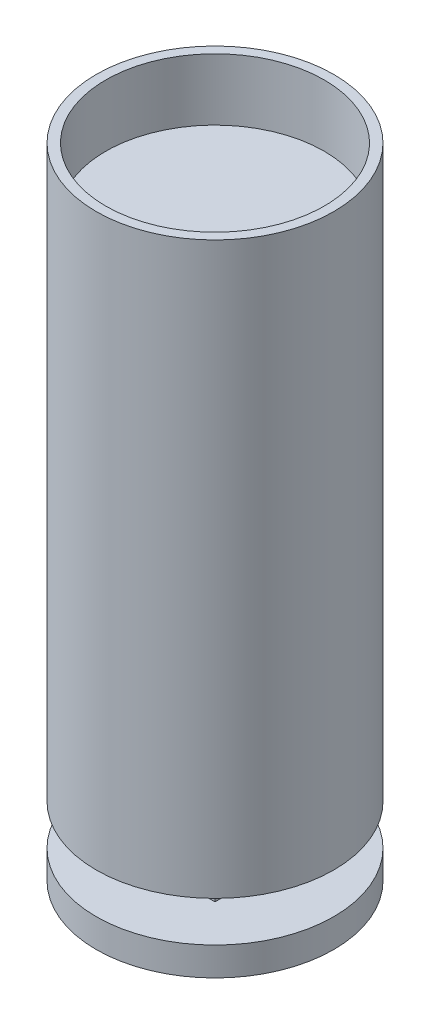
SolidWorks part; units mm, degrees
ref_plane "Front Plane" through (0, 0, 0) normal (0, 0, 1) x (1, 0, 0)
ref_plane "Top Plane" through (0, 0, 0) normal (0, 1, 0) x (1, 0, 0)
ref_plane "Right Plane" through (0, 0, 0) normal (1, 0, 0) x (0, 0, -1)
sketch "Sketch1" plane through (0, 0, 0) normal (0, 1, 0) x (1, 0, 0)
  line L0 (0, 12.3074) -> (0, -10.2003) construction
  line L1 (-13.6004, 0) -> (10.8228, 0) construction
  line L7 (8.8388, -8.8388) -> (-8.8388, 8.8388) construction
  line L8 (8.8388, 8.8388) -> (-8.8388, -8.8388) construction
  circle A0 centre (0, 0) radius 12.5
  dimension "D1" = 25
extrude "Boss-Extrude1" add sketch "Sketch1" along normal mid plane 3
sketch "Sketch2" plane through (0, 1.5, 0) normal (0, 1, 0) x (1, 0, 0)
  line L1 (4.9, -4.9) -> (-4.9, -4.9)
  line L2 (4.9, -4.9) -> (4.9, 4.9)
  line L3 (4.9, 4.9) -> (-4.9, 4.9)
  line L4 (-4.9, -4.9) -> (-4.9, 4.9)
  line L5 (4.9, -4.9) -> (-4.9, 4.9) construction
  line L6 (4.9, 4.9) -> (-4.9, -4.9) construction
  point P0 (0, 0)
  dimension "D1" = 9.8
  dimension "D2" = 9.8
extrude "Boss-Extrude2" add sketch "Sketch2" along normal blind 4.25
ref_plane "Plane1" through (0, 3.625, 0) normal (0, 1, 0) x (1, 0, 0)
mirror "Mirror1" about plane through (0, 3.625, 0) normal (0, 1, 0) of "Boss-Extrude1"
sketch "Sketch3" plane through (0, 8.75, 0) normal (0, 1, 0) x (1, 0, 0)
  circle A0 centre (0, 0) radius 12.5
  point P0 (0, 0)
  dimension "D1" = 25
extrude "Boss-Extrude3" add sketch "Sketch3" along normal blind 47.5
sketch "Sketch4" plane through (0, 56.25, 0) normal (0, 1, 0) x (1, 0, 0)
  circle A0 centre (0, 0) radius 12.5
  dimension "D1" = 25
extrude "Boss-Extrude4" add sketch "Sketch4" along normal blind 3
sketch "Sketch5" plane through (0, 59.25, 0) normal (0, 1, 0) x (1, 0, 0)
  circle A0 centre (0, 0) radius 11.5
  circle A1 centre (0, 0) radius 12.5
  dimension "D1" = 23
extrude "Boss-Extrude5" add sketch "Sketch5" along normal blind 6.5
